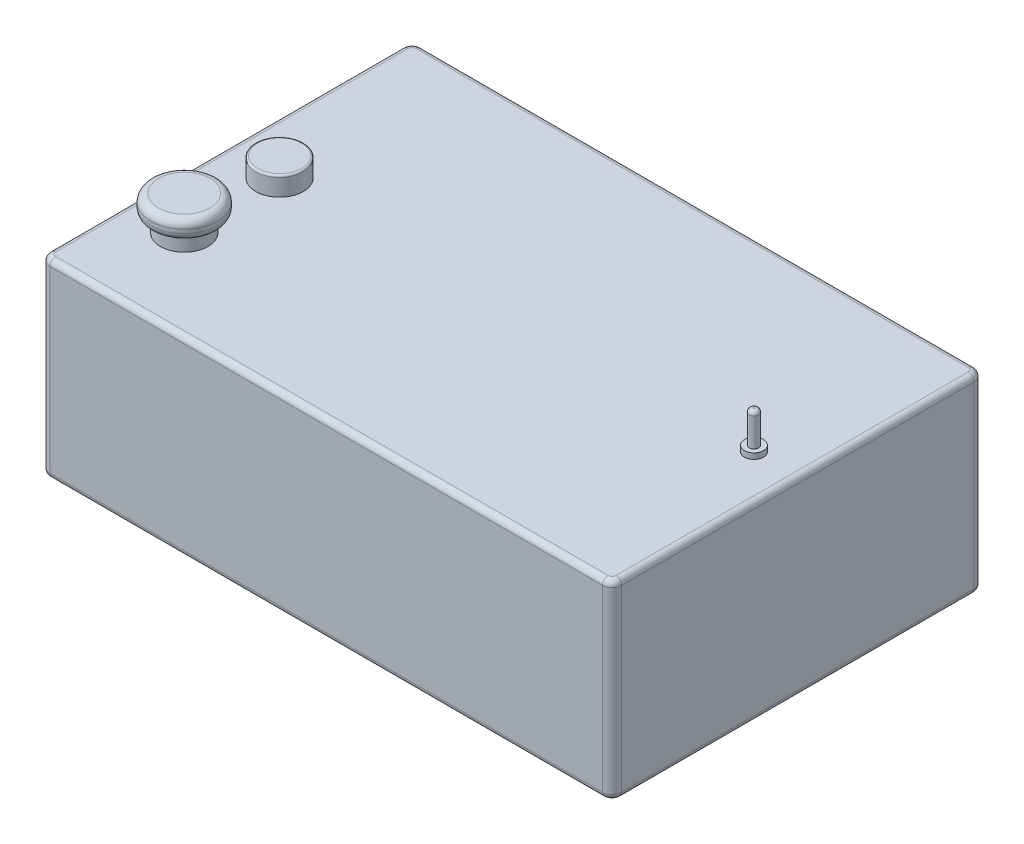
SolidWorks part; units mm, degrees
ref_plane "Front Plane" through (0, 0, 0) normal (0, 0, 1) x (1, 0, 0)
ref_plane "Top Plane" through (0, 0, 0) normal (0, 1, 0) x (1, 0, 0)
ref_plane "Right Plane" through (0, 0, 0) normal (1, 0, 0) x (0, 0, -1)
sketch "Sketch2" plane through (0, 0, 0) normal (0, 1, 0) x (1, 0, 0)
  line L1 (-145, 97.5) -> (145, 97.5)
  line L2 (-150, 92.5) -> (-150, -92.5)
  line L3 (-145, -97.5) -> (145, -97.5)
  line L4 (150, 92.5) -> (150, -92.5)
  line L5 (-150, 97.5) -> (150, -97.5) construction
  line L6 (-150, -97.5) -> (150, 97.5) construction
  arc A0 (-150, -92.5) -> (-145, -97.5) centre (-145, -92.5) ccw
  arc A1 (145, -97.5) -> (150, -92.5) centre (145, -92.5) ccw
  arc A2 (145, 97.5) -> (150, 92.5) centre (145, 92.5) cw
  arc A3 (-145, 97.5) -> (-150, 92.5) centre (-145, 92.5) ccw
  point P0 (0, 0)
  dimension "D3" = 5
  dimension "D1" = 195
  dimension "D2" = 300
extrude "Boss-Extrude1" add sketch "Sketch2" along normal blind 100
fillet "Fillet3" radius 3 16 edges at (148.5355, 100, -96.0355) (0, 100, -97.5) (-148.5355, 100, -96.0355) (-150, 100, 0) (-148.5355, 100, 96.0355) (0, 100, 97.5) (148.5355, 100, 96.0355) (150, 100, 0) (0, 0, 97.5) (148.5355, 0, 96.0355) (150, 0, 0) (148.5355, 0, -96.0355) (0, 0, -97.5) (-148.5355, 0, -96.0355) (-150, 0, 0) (-148.5355, 0, 96.0355)
sketch "Sketch3" plane through (0, 100, 0) normal (0, 1, 0) x (1, 0, 0)
  line L0 (0, 0) -> (-147, 0) construction
  line L1 (-147, 92.5) -> (-147, -92.5) construction
  circle A0 centre (-122, 0) radius 12.5
  dimension "D1" = 25
  dimension "D2" = 25
extrude "Boss-Extrude2" add sketch "Sketch3" along normal blind 10
sketch "Sketch4" plane through (0, 100, 0) normal (0, 1, 0) x (1, 0, 0)
  line L1 (-95.1629, -50) -> (-147, -50) construction
  line L2 (-147, 92.5) -> (-147, -92.5) construction
  line L3 (-122, 0) -> (-122, -50) construction
  circle A0 centre (-122, -50) radius 12.5
  point P9 (-122, -42.8381)
  point P10 (-122, 0)
  point P11 (-122, 0)
  dimension "D1" = 25
  dimension "D2" = 50
extrude "Boss-Extrude3" add sketch "Sketch4" along normal blind 8
sketch "Sketch5" plane through (0, 108, 0) normal (0, 1, 0) x (1, 0, 0)
  circle A0 centre (-122, -50) radius 17.5
  dimension "D1" = 35
extrude "Boss-Extrude5" add sketch "Sketch5" along normal blind 10
fillet "Fillet6" radius 4 2 edges at (-122, 108, 67.5) (-122, 118, 67.5)
fillet "Fillet7" radius 1 1 edges at (-122, 110, 12.5)
sketch "Sketch6" plane through (0, 100, 0) normal (0, 1, 0) x (1, 0, 0)
  line L0 (0, 0) -> (147, 0) construction
  line L1 (147, -92.5) -> (147, 92.5) construction
  circle A0 centre (127, 0) radius 5
  dimension "D1" = 10
  dimension "D2" = 20
extrude "Boss-Extrude6" add sketch "Sketch6" along normal blind 3
sketch "Sketch7" plane through (0, 103, 0) normal (0, 1, 0) x (1, 0, 0)
  circle A0 centre (127, 0) radius 2.5
  dimension "D1" = 5
extrude "Boss-Extrude7" add sketch "Sketch7" along normal blind 17
fillet "Fillet13" radius 2 1 edges at (127, 120, 2.5)
